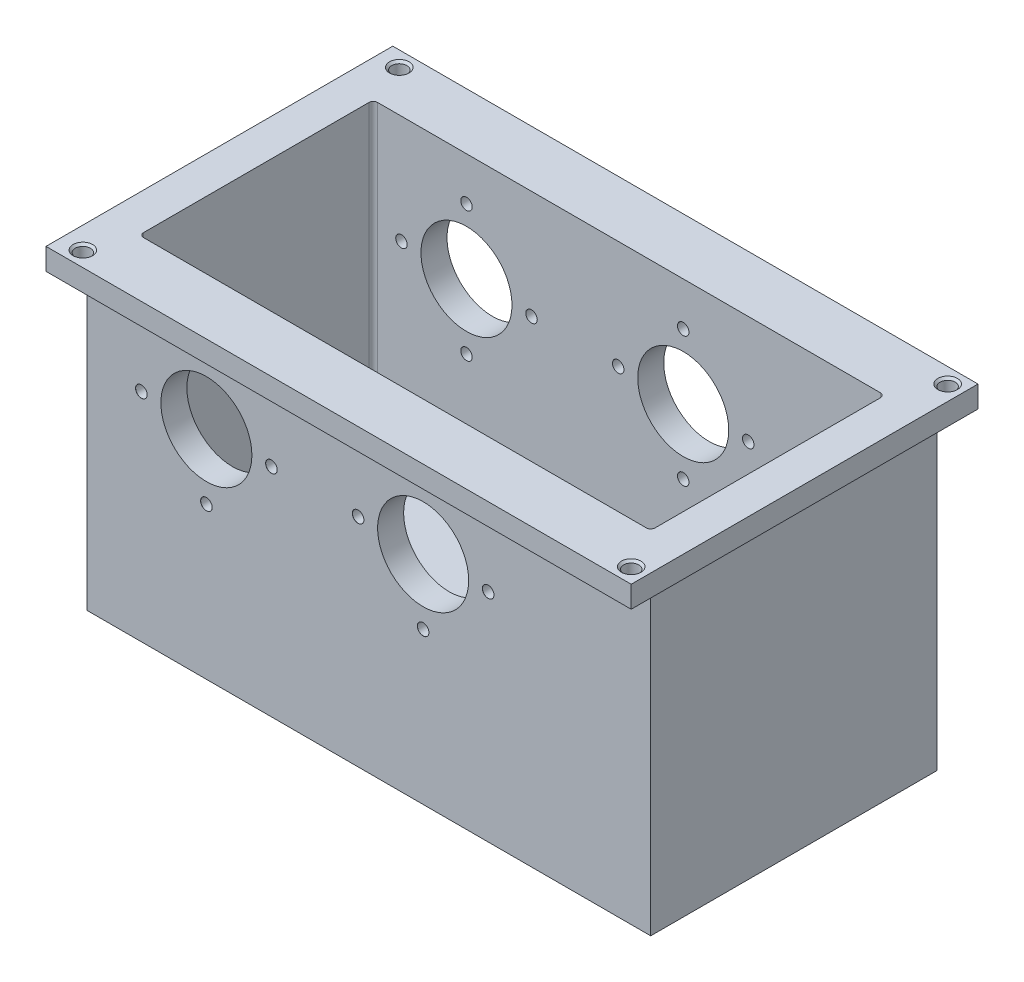
SolidWorks part; units mm, degrees
material "1060 Alloy"
ref_plane "Front Plane" through (0, 0, 0) normal (0, 0, 1) x (1, 0, 0)
ref_plane "Top Plane" through (0, 0, 0) normal (0, 1, 0) x (1, 0, 0)
ref_plane "Right Plane" through (0, 0, 0) normal (1, 0, 0) x (0, 0, -1)
sketch "Sketch1" plane through (0, 0, 0) normal (0, 1, 0) x (1, 0, 0)
  line L1 (130, 66) -> (-130, 66)
  line L2 (130, 66) -> (130, -66)
  line L3 (130, -66) -> (-130, -66)
  line L4 (-130, 66) -> (-130, -66)
  line L5 (130, 66) -> (-130, -66) construction
  line L6 (130, -66) -> (-130, 66) construction
  point P0 (0, 0)
  dimension "D1" = 260
  dimension "D2" = 132
extrude "Boss-Extrude1" add sketch "Sketch1" along normal blind 150
shell "Shell1" thickness 12
sketch "Sketch2" plane through (0, 150, 0) normal (0, 1, 0) x (1, 0, 0)
  line L1 (135, -80) -> (-135, -80)
  line L2 (135, -80) -> (135, 80)
  line L3 (135, 80) -> (-135, 80)
  line L4 (-135, -80) -> (-135, 80)
  line L5 (135, -80) -> (-135, 80) construction
  line L6 (135, 80) -> (-135, -80) construction
  line L8 (130, -66) -> (130, 66) construction
  line L9 (-130, -66) -> (130, -66) construction
  line L10 (-130, 66) -> (-130, -66) construction
  line L11 (130, 66) -> (-130, 66) construction
  line L12 (130, -66) -> (130, 66)
  line L13 (-130, -66) -> (130, -66)
  line L14 (-130, 66) -> (-130, -66)
  line L15 (130, 66) -> (-130, 66)
  point P0 (0, 0)
  dimension "D1" = 270
  dimension "D2" = 160
extrude "Boss-Extrude2" add sketch "Sketch2" against normal blind 10
sketch "Sketch3" plane through (0, 150, 0) normal (0, 1, 0) x (1, 0, 0)
  line L0 (135, 80) -> (-135, 80) construction
  line L1 (-135, 0) -> (135, 0) construction
  line L2 (-135, 80) -> (-135, -80) construction
  line L3 (135, -80) -> (135, 80) construction
  circle A0 centre (-125, 73) radius 3.5
  circle A4 centre (128, 73) radius 3.5
  circle A5 centre (128, -73) radius 3.5
  circle A9 centre (-125, -73) radius 3.5
  circle A10 centre (-61.75, 73) radius 3.5 [skipped]
  circle A11 centre (64.75, 73) radius 3.5 [skipped]
  circle A14 centre (1.5, 73) radius 3.5 [skipped]
  dimension "D1" = 7
  dimension "D2" = 7
  dimension "D3" = 10
  dimension "D7" = 7
  dimension "D4" = 5
extrude "Cut-Extrude1" cut sketch "Sketch3" against normal up to surface (10 mm away) up to face at (0, 140, 0)
sketch "Sketch4" plane through (0, 0, 66) normal (0, 0, 1) x (1, 0, 0)
  line L0 (-135, 150) -> (135, 150) construction
  line L2 (-130, 140) -> (-130, 0) construction
  circle A0 centre (-75, 100) radius 21
  circle A1 centre (25, 100) radius 21
  dimension "D1" = 42
  dimension "D2" = 50
  dimension "D3" = 100
  dimension "D4" = 55
extrude "Cut-Extrude2" cut sketch "Sketch4" against normal up to surface (132 mm away) up to face at (0, 70, -66)
chamfer "Chamfer1" distance 1 angle 45 4 edges at (128, 150, -69.5) (128, 150, 69.5) (-125, 150, 69.5) (-125, 150, -69.5)
fillet "Fillet1" radius 2 8 edges at (0, 12, -54) (118, 12, 0) (0, 12, 54) (-118, 12, 0) (118, 81, 54) (118, 81, -54) (-118, 81, 54) (-118, 81, -54)
sketch "Sketch5" plane through (0, 0, 66) normal (0, 0, 1) x (1, 0, 0)
  circle A0 centre (-75, 100) radius 30 construction
  circle A1 centre (25, 100) radius 30 construction
  point P3 (-75, 130)
  point P4 (-105, 100)
  point P5 (-75, 70)
  point P6 (-45, 100)
  point P10 (25, 130)
  point P11 (-5, 100)
  point P12 (25, 70)
  point P13 (55, 100)
  dimension "D1" = 60
hole_wizard "M5 Clearance Hole1" positions "Sketch5" profile "Sketch6" hole size "M5" standard "ISO" end condition through all
sketch "Sketch6" plane through (55, 100, 66) normal (1, 0, 0) x (0, -1, 0)
  line L0 (0, 0) -> (0, 146)
  line L1 (0, 146) -> (2.65, 146)
  line L2 (2.65, 146) -> (2.65, 0.025)
  line L3 (2.65, 0.025) -> (2.675, 0)
  line L5 (2.675, 0) -> (0, 0)
  line L6 (-2.65, 0.025) -> (-2.675, 0) construction
  line L11 (0, -6.35) -> (0, 107.95) construction
  dimension "Thru Hole Dia." = 5.3
  dimension "Thru Hole Depth" = 146
  dimension "Near C'Sink Dia." = 5.35
  dimension "Near C'Sink Angle" = 90
